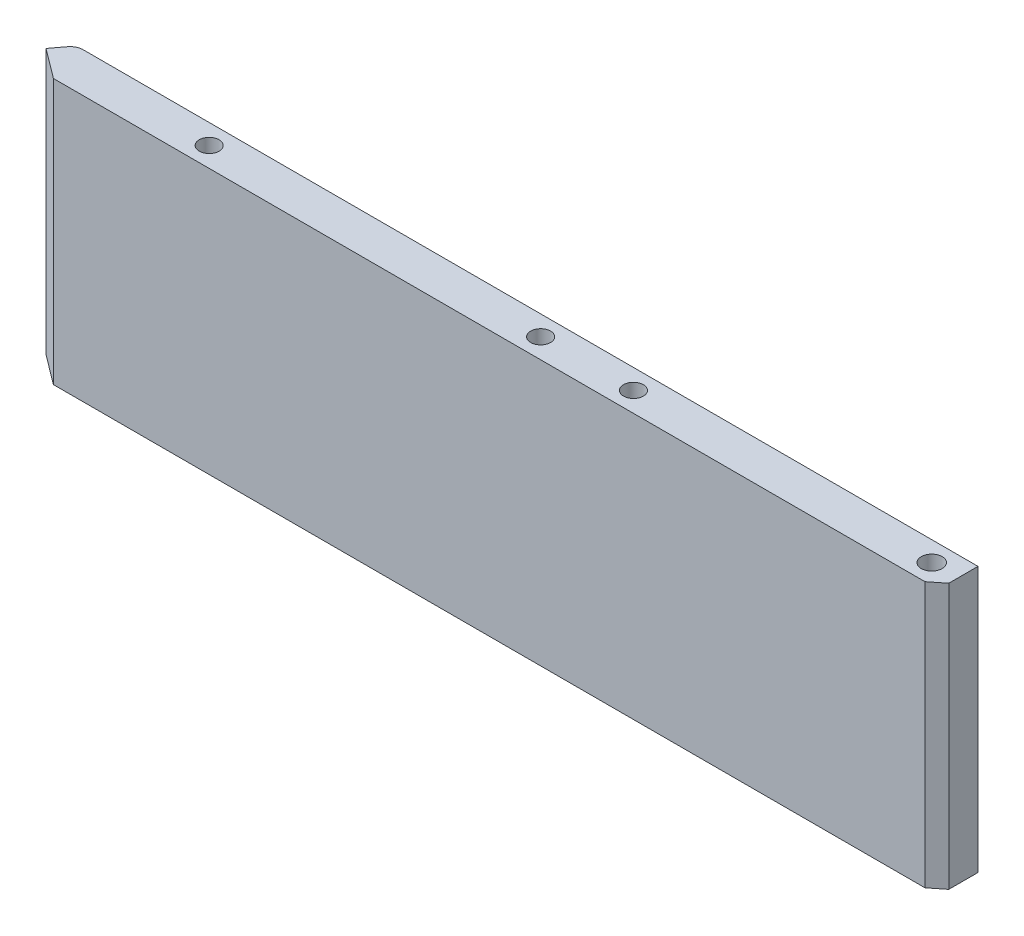
SolidWorks part; units mm, degrees
ref_plane "Front Plane" through (0, 0, 0) normal (0, 0, 1) x (1, 0, 0)
ref_plane "Top Plane" through (0, 0, 0) normal (0, 1, 0) x (1, 0, 0)
ref_plane "Right Plane" through (0, 0, 0) normal (1, 0, 0) x (0, 0, -1)
sketch "Sketch1" plane through (0, 0, 0) normal (0, 1, 0) x (1, 0, 0)
  line L0 (-110, 0) -> (-80, 40)
  line L1 (-80, 40) -> (80, 40)
  line L3 (77.5, 34) -> (-77.5, 34)
  line L4 (-77.5, 34) -> (-103, 0)
  line L5 (-103, 0) -> (-110, 0)
  line L6 (0, -55) -> (0, 55) construction
  line L7 (103, 0) -> (110, 0)
  line L8 (77.5, 34) -> (103, 0)
  line L9 (110, 0) -> (80, 40)
  dimension "D1" = 6
  dimension "D2" = 7
  dimension "D3" = 40
  dimension "D4" = 30
extrude "Boss-Extrude1" add sketch "Sketch1" along normal mid plane 40
sketch "Sketch2" plane through (0, 20, 0) normal (0, 1, 0) x (1, 0, 0)
  line L1 (-80, 40) -> (-110, 0) construction
  line L2 (80, 40) -> (-80, 40) construction
  line L3 (0, -22) -> (0, 22) construction
  circle A0 centre (-104, 3) radius 1.5
  circle A1 centre (-57, 37) radius 1.5
  circle A2 centre (-7, 37) radius 1.5
  circle A3 centre (7, 37) radius 1.5
  circle A5 centre (104, 3) radius 1.5
  circle A6 centre (52, 37) radius 1.5725
  dimension "D2" = 3
  dimension "D3" = 3
  dimension "D5" = 3
  dimension "D1" = 50
  dimension "D4" = 7
  dimension "D6" = 3
  dimension "D7" = 3
  dimension "D8" = 3
  dimension "D9" = 37
  dimension "D10" = 45
extrude "Cut-Extrude1" cut sketch "Sketch2" against normal blind 5
fillet "Fillet1" radius 2 2 edges at (80, 0, -40) (-80, 0, -40)
sketch "Sketch3" plane through (-65.92, 0, -49.44) normal (0.8, 0, 0.6) x (0.6, 0, -0.8)
  line L1 (-19.3, -20) -> (-123.0845, -20)
  line L2 (-19.3, -20) -> (-19.3, 53.7488)
  line L3 (-19.3, 53.7488) -> (-123.0845, 53.7488)
  line L4 (-123.0845, -20) -> (-123.0845, 53.7488)
extrude "Cut-Extrude2" cut sketch "Sketch3" against normal through all both and the other way through all
mirror "Mirror1" about plane through (0, 0, 0) normal (1, 0, 0) of "Cut-Extrude2"
sketch "Sketch4" plane through (0, 0, -34) normal (0, 0, 1) x (1, 0, 0)
  line L0 (-77.5, 20) -> (77.5, 20) construction
  line L1 (81.98, -20) -> (55.98, -20)
  line L2 (81.98, -20) -> (81.98, 20)
  line L3 (81.98, 20) -> (55.98, 20)
  line L4 (55.98, -20) -> (55.98, 20)
  dimension "D1" = 26
extrude "Cut-Extrude3" cut sketch "Sketch4" against normal through all both and the other way through all
sketch "Sketch5" plane through (0, -20, 0) normal (0, -1, 0) x (1, 0, 0)
  line L0 (55.98, -35.588) -> (53.98, -34)
  line L1 (55.98, -40) -> (55.98, -34) construction
  line L2 (-77.5, -34) -> (55.98, -34) construction
  line L3 (53.98, -34) -> (55.98, -34)
  line L4 (55.98, -34) -> (55.98, -35.588)
  dimension "D1" = 38.45
  dimension "D3" = 2
extrude "Cut-Extrude4" cut sketch "Sketch5" against normal through all both and the other way through all
